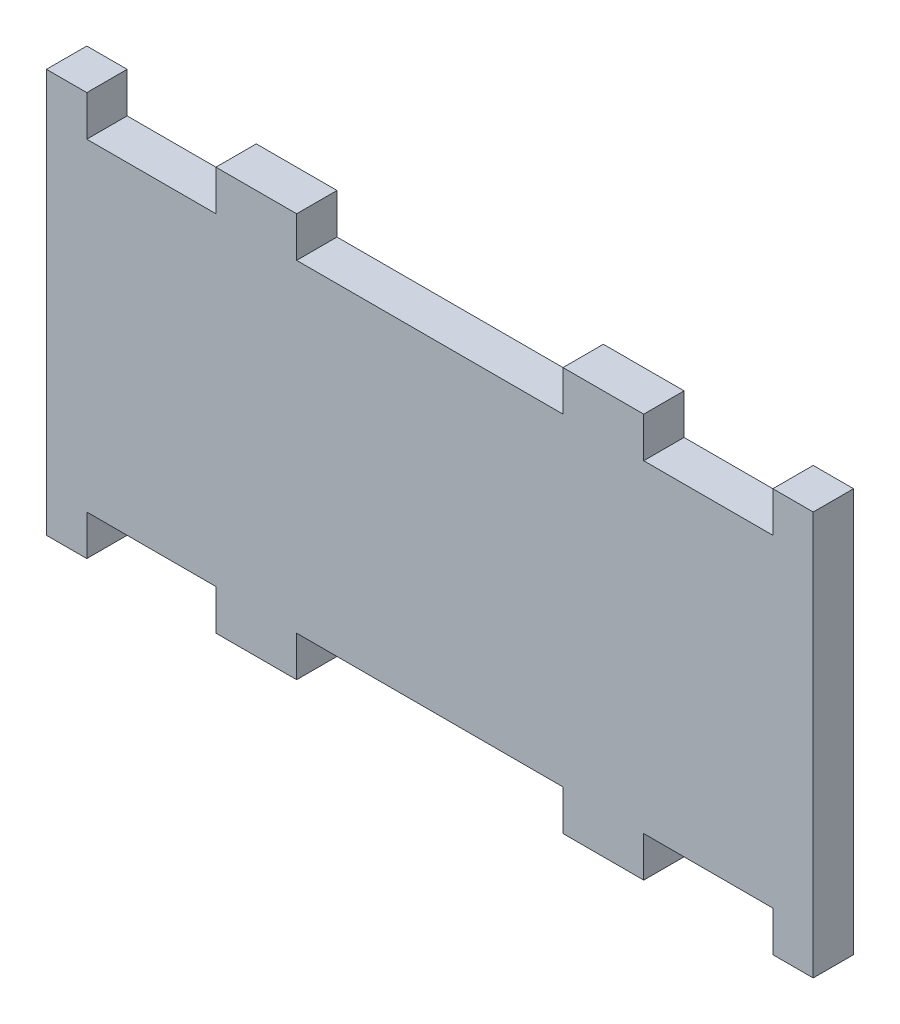
SolidWorks part; units mm, degrees
ref_plane "Front Plane" through (0, 0, 0) normal (0, 0, 1) x (1, 0, 0)
ref_plane "Top Plane" through (0, 0, 0) normal (0, 1, 0) x (1, 0, 0)
ref_plane "Right Plane" through (0, 0, 0) normal (1, 0, 0) x (0, 0, -1)
sketch "Sketch1" plane through (0, 0, 0) normal (0, 0, 1) x (1, 0, 0)
  line L1 (0, 0) -> (120.65, 0)
  line L2 (0, 0) -> (0, 63.5)
  line L3 (0, 63.5) -> (120.65, 63.5)
  line L4 (120.65, 0) -> (120.65, 63.5)
  dimension "D1" = 120.65
  dimension "D2" = 63.5
extrude "Boss-Extrude1" add sketch "Sketch1" along normal blind 6.35 contours L3 L4 L1 L2
sketch "Sketch2" plane through (0, 0, 6.35) normal (0, 0, 1) x (1, 0, 0)
  line L0 (0, 63.5) -> (120.65, 63.5) construction
  line L1 (6.35, 63.5) -> (26.67, 63.5)
  line L2 (6.35, 63.5) -> (6.35, 57.15)
  line L3 (6.35, 57.15) -> (26.67, 57.15)
  line L4 (26.67, 63.5) -> (26.67, 57.15)
  line L5 (0, 0) -> (0, 63.5) construction
  line L7 (39.37, 63.5) -> (81.28, 63.5)
  line L8 (39.37, 63.5) -> (39.37, 57.15)
  line L9 (39.37, 57.15) -> (81.28, 57.15)
  line L10 (81.28, 63.5) -> (81.28, 57.15)
  line L15 (26.67, 60.325) -> (39.37, 60.325) construction
  line L16 (60.325, 63.5) -> (60.325, 57.15) construction
  line L17 (114.3, 57.15) -> (93.98, 57.15)
  line L18 (93.98, 63.5) -> (93.98, 57.15)
  line L19 (114.3, 63.5) -> (93.98, 63.5)
  line L20 (114.3, 63.5) -> (114.3, 57.15)
  line L21 (120.65, 0) -> (120.65, 63.5) construction
  line L22 (0, 31.75) -> (120.65, 31.75) construction
  line L23 (114.3, 0) -> (114.3, 6.35)
  line L24 (114.3, 0) -> (93.98, 0)
  line L25 (93.98, 0) -> (93.98, 6.35)
  line L26 (114.3, 6.35) -> (93.98, 6.35)
  line L27 (39.37, 6.35) -> (81.28, 6.35)
  line L28 (81.28, 0) -> (81.28, 6.35)
  line L29 (39.37, 0) -> (81.28, 0)
  line L30 (39.37, 0) -> (39.37, 6.35)
  line L31 (6.35, 6.35) -> (26.67, 6.35)
  line L32 (26.67, 0) -> (26.67, 6.35)
  line L33 (6.35, 0) -> (26.67, 0)
  line L34 (6.35, 0) -> (6.35, 6.35)
  dimension "D1" = 6.35
  dimension "D2" = 6.35
  dimension "D3" = 12.7
  dimension "D4" = 6.35
  dimension "D6" = 20.32
extrude "Cut-Extrude1" cut sketch "Sketch2" against normal up to next
